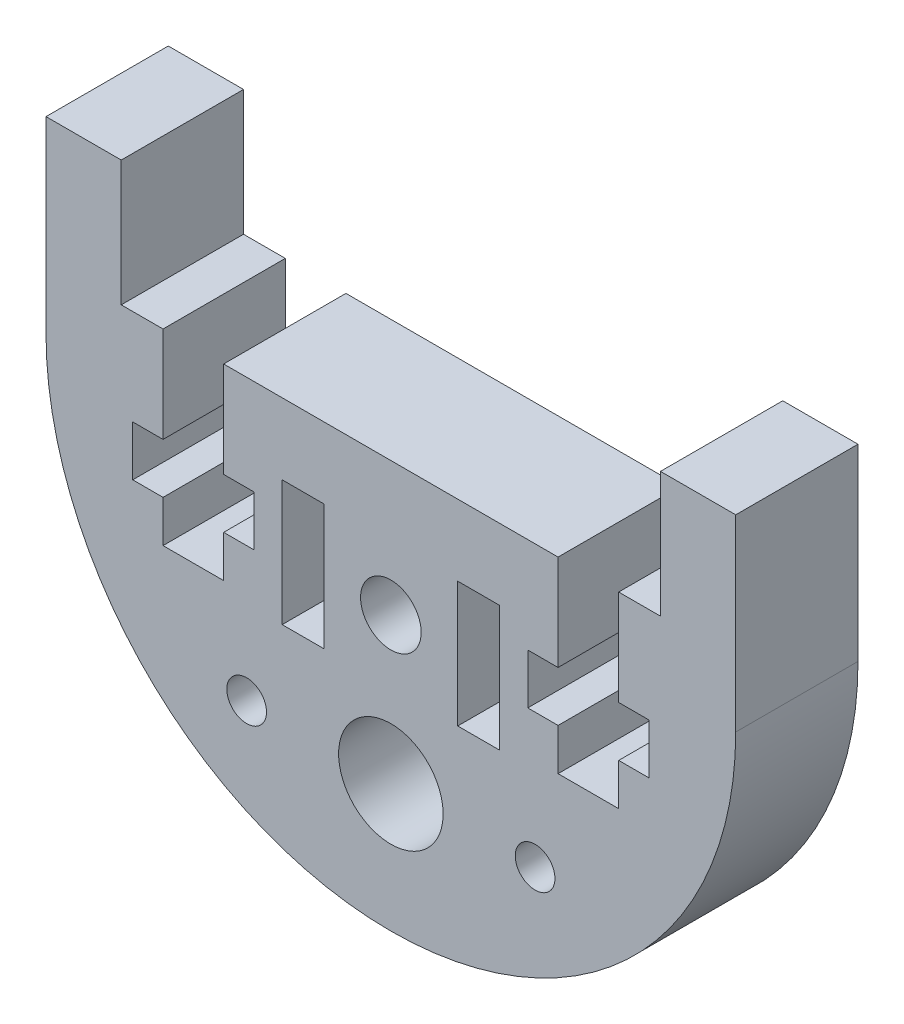
SolidWorks part; units mm, degrees
material "Acrylic (Medium-high impact)"
ref_plane "Front Plane" through (0, 0, 0) normal (0, 0, 1) x (1, 0, 0)
ref_plane "Top Plane" through (0, 0, 0) normal (0, 1, 0) x (1, 0, 0)
ref_plane "Right Plane" through (0, 0, 0) normal (1, 0, 0) x (0, 0, -1)
sketch "Model" plane through (0, 0, 0) normal (0, 0, 1) x (1, 0, 0)
  line L0 (545.5095, 560.9325) -> (553.5095, 560.9325)
  line L1 (553.5095, 547.5325) -> (553.5095, 543.2575) construction
  line L2 (553.5095, 547.5325) -> (553.5095, 543.2575) construction
  line L3 (546.6095, 547.5325) -> (553.5095, 547.5325) construction
  line L4 (560.4095, 547.5325) -> (553.5095, 547.5325) construction
  line L5 (553.5095, -441.0675) -> (553.5095, 49558.9325) construction
  line L6 (553.5095, 547.5325) -> (553.5095, 543.2575) construction
  line L7 (553.5095, 543.2575) -> (553.5095, 547.5325) construction
  line L8 (561.5095, 556.3566) -> (561.5095, 560.9325)
  line L9 (560.0595, 556.3566) -> (561.5095, 556.3566)
  line L10 (560.0595, 553.9565) -> (560.0595, 556.3566)
  line L11 (561.5095, 553.9565) -> (560.0595, 553.9565)
  line L12 (561.5095, 551.9565) -> (561.5095, 553.9565)
  line L13 (564.4095, 551.9565) -> (561.5095, 551.9565)
  line L14 (564.4095, 553.9565) -> (564.4095, 551.9565)
  line L15 (565.8595, 553.9565) -> (564.4095, 553.9565)
  line L16 (565.8595, 556.3566) -> (565.8595, 553.9565)
  line L17 (564.4095, 556.3566) -> (565.8595, 556.3566)
  line L18 (564.4095, 560.9325) -> (564.4095, 556.3566)
  line L19 (566.4095, 560.9325) -> (564.4095, 560.9325)
  line L20 (566.4095, 566.9325) -> (566.4095, 560.9325)
  line L21 (570.0095, 566.9325) -> (566.4095, 566.9325)
  line L22 (570.0095, 557.9325) -> (570.0095, 566.9325)
  line L23 (561.5095, 560.9325) -> (553.5095, 560.9325)
  line L24 (553.5095, 547.5325) -> (553.5095, 555.4893) construction
  line L25 (542.6095, 560.9325) -> (545.5095, 560.9325) construction
  line L26 (544.0595, 560.9325) -> (544.0595, 551.9565) construction
  line L27 (562.9595, 560.9325) -> (562.9595, 551.9565) construction
  line L28 (561.5095, 560.9325) -> (564.4095, 560.9325) construction
  line L29 (558.7095, 551.5325) -> (556.7095, 551.5325)
  line L30 (548.3095, 551.5325) -> (550.3095, 551.5325)
  line L31 (548.3095, 551.5325) -> (548.3095, 557.5325)
  line L32 (548.3095, 557.5325) -> (550.3095, 557.5325)
  line L33 (550.3095, 551.5325) -> (550.3095, 557.5325)
  line L34 (558.7095, 551.5325) -> (558.7095, 557.5325)
  line L35 (558.7095, 557.5325) -> (556.7095, 557.5325)
  line L36 (556.7095, 551.5325) -> (556.7095, 557.5325)
  line L41 (537.0095, 557.9325) -> (537.0095, 566.9325)
  line L42 (537.0095, 566.9325) -> (540.6095, 566.9325)
  line L43 (540.6095, 566.9325) -> (540.6095, 560.9325)
  line L44 (540.6095, 560.9325) -> (542.6095, 560.9325)
  line L45 (542.6095, 560.9325) -> (542.6095, 556.3566)
  line L46 (542.6095, 556.3566) -> (541.1595, 556.3566)
  line L47 (541.1595, 556.3566) -> (541.1595, 553.9565)
  line L48 (541.1595, 553.9565) -> (542.6095, 553.9565)
  line L49 (542.6095, 553.9565) -> (542.6095, 551.9565)
  line L50 (542.6095, 551.9565) -> (545.5095, 551.9565)
  line L51 (545.5095, 551.9565) -> (545.5095, 553.9565)
  line L52 (545.5095, 553.9565) -> (546.9595, 553.9565)
  line L53 (546.9595, 553.9565) -> (546.9595, 556.3566)
  line L54 (546.9595, 556.3566) -> (545.5095, 556.3566)
  line L55 (545.5095, 556.3566) -> (545.5095, 560.9325)
  circle A0 centre (546.6095, 547.5325) radius 0.95
  circle A1 centre (553.5095, 547.5325) radius 2.5
  circle A2 centre (553.5095, 554.5325) radius 1.45
  arc A4 (570.0095, 557.9325) -> (537.0095, 557.9325) centre (553.5095, 557.9325) cw
  circle A8 centre (560.4095, 547.5325) radius 0.95
  point P7 (544.0595, 560.9325)
  point P18 (553.5095, 554.5325)
  point P41 (550.3095, 554.5325)
  point P42 (552.0595, 554.5325)
  point P47 (556.7095, 554.5325)
  point P48 (553.5095, 550.0325)
  dimension "D10" = 6.9
  dimension "D9" = 1.9
  dimension "D14" = 5
  dimension "D16" = 2.9
  dimension "D1" = 3.6
  dimension "D2" = 6
  dimension "D3" = 9
  dimension "D4" = 2.4001
  dimension "D5" = 1.45
  dimension "D6" = 4.5759
  dimension "D7" = 2
  dimension "D8" = 2
  dimension "D11" = 8
  dimension "D12" = 4
  dimension "D13" = 2.9
  dimension "D15" = 3.4
  dimension "D17" = 2
  dimension "D18" = 6
  dimension "D19" = 1.75
  dimension "D20" = 1.35
extrude "Boss-Extrude2" add sketch "Model" along normal blind 5.85
